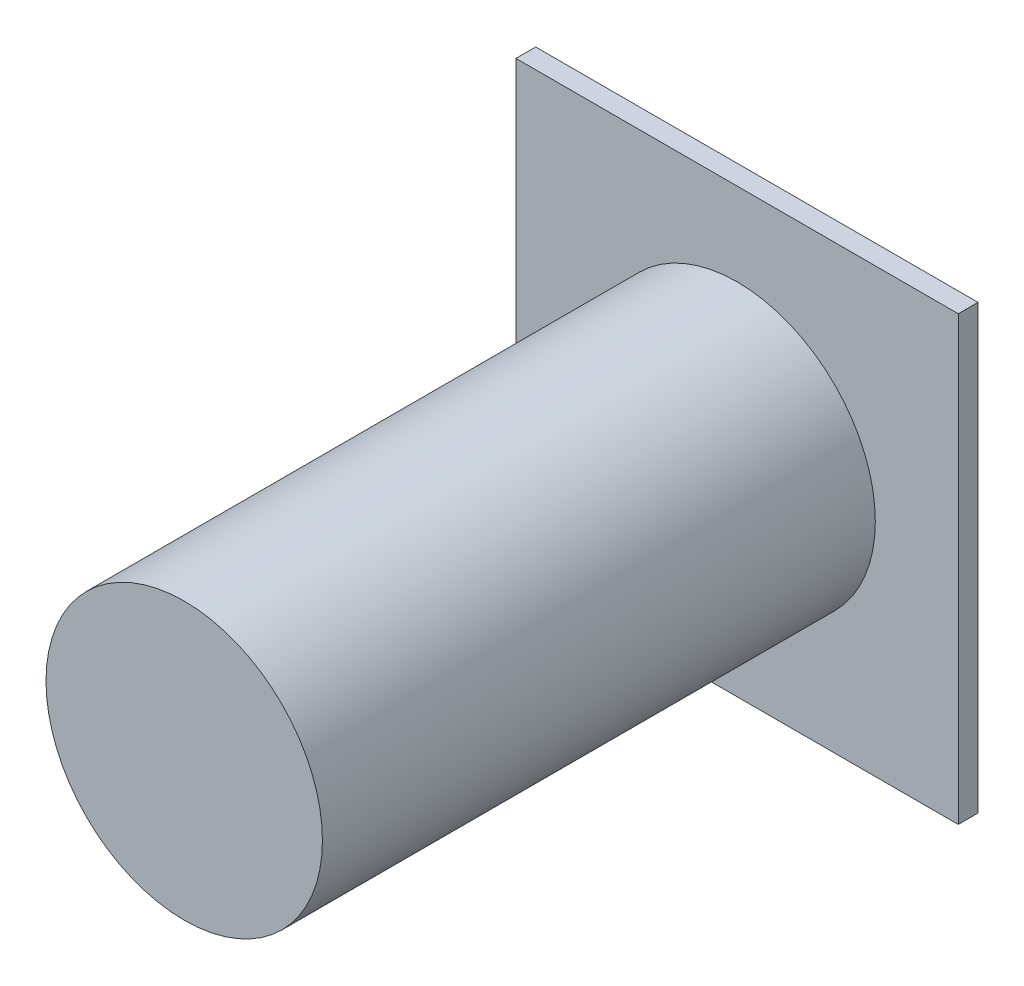
SolidWorks part; units mm, degrees
ref_plane "Front Plane" through (0, 0, 0) normal (0, 0, 1) x (1, 0, 0)
ref_plane "Top Plane" through (0, 0, 0) normal (0, 1, 0) x (1, 0, 0)
ref_plane "Right Plane" through (0, 0, 0) normal (1, 0, 0) x (0, 0, -1)
sketch "Sketch1" plane through (0, 0, 0) normal (0, 0, 1) x (1, 0, 0)
  line L1 (-28, 28) -> (28, 28)
  line L2 (-28, 28) -> (-28, -28)
  line L3 (-28, -28) -> (28, -28)
  line L4 (28, 28) -> (28, -28)
  dimension "D1" = 56
  dimension "D2" = 56
  dimension "D3" = 28
  dimension "D4" = 28
extrude "Boss-Extrude1" add sketch "Sketch1" along normal blind 2.5
sketch "Sketch2" plane through (0, 0, 2.5) normal (0, 0, 1) x (1, 0, 0)
  circle A0 centre (0, 0) radius 17.5
  dimension "D1" = 35
extrude "Boss-Extrude2" add sketch "Sketch2" along normal blind 70
